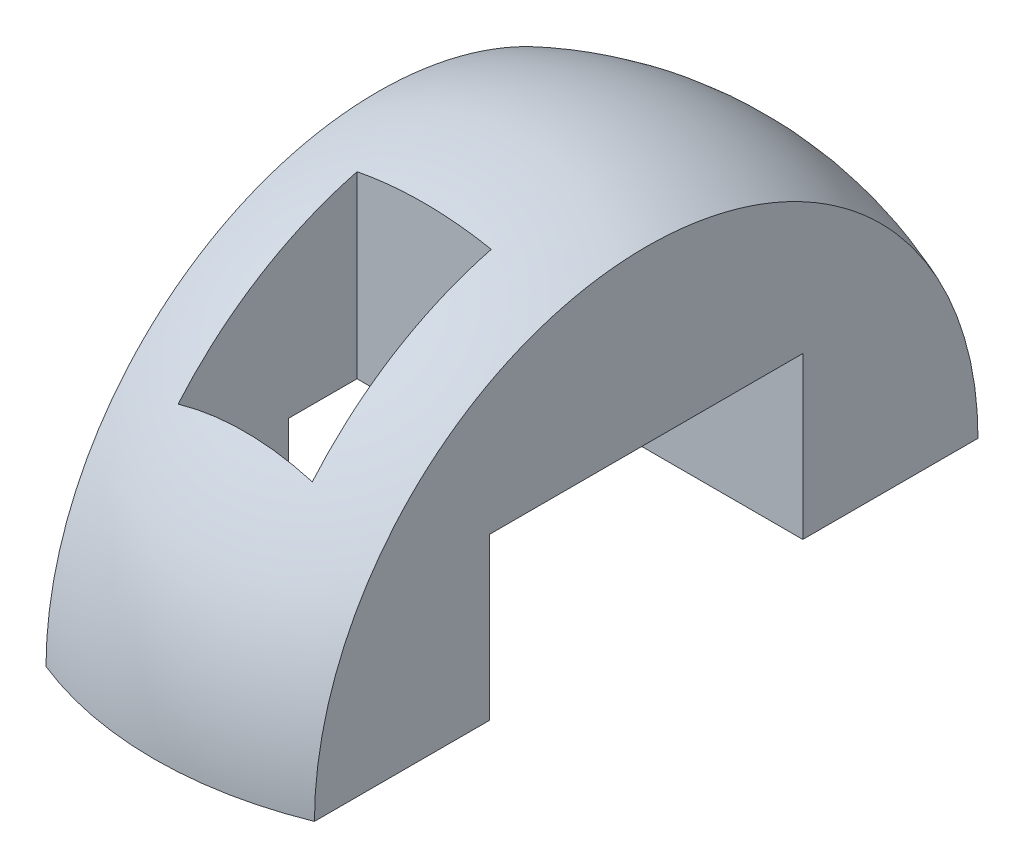
SolidWorks part; units mm, degrees
ref_plane "Front Plane" through (0, 0, 0) normal (0, 0, 1) x (1, 0, 0)
ref_plane "Top Plane" through (0, 0, 0) normal (0, 1, 0) x (1, 0, 0)
ref_plane "Right Plane" through (0, 0, 0) normal (1, 0, 0) x (0, 0, -1)
sketch "Sketch1" plane through (0, 0, 0) normal (0, 0, 1) x (1, 0, 0)
  line L0 (0, 0) -> (80, 0)
  line L1 (0, 0) -> (0, 80) construction
  line L2 (0, 0) -> (0, 80)
  line L3 (0, 80) -> (0, 0)
  arc A1 (80, 0) -> (0, 80) centre (0, 0) ccw
  dimension "D2" = 80
revolve "Revolve2" add sketch "Sketch1" angle 360 about L2
ref_plane "Plane1" through (0, 0, 80) normal (0, 0, 1) x (1, 0, 0)
sketch "Sketch2" plane through (0, 0, 80) normal (0, 0, 1) x (1, 0, 0)
  line L0 (-80, 0) -> (80, 0) construction
  line L1 (80, 0) -> (0, 0)
  line L2 (80, 0) -> (80, 80)
  line L3 (80, 80) -> (0, 80)
  line L4 (0, 0) -> (0, 80)
  line L5 (0, 80) -> (-80, 80)
  line L6 (0, 80) -> (0, 0)
  line L7 (0, 0) -> (-80, 0)
  line L8 (-80, 80) -> (-80, 0)
  line L10 (30, 0) -> (-30, 0)
  line L11 (30, 0) -> (30, 80)
  line L12 (30, 80) -> (-30, 80)
  line L13 (-30, 0) -> (-30, 80)
  arc A0 (80, 0) -> (-80, 0) centre (0, 0) ccw construction
  dimension "D1" = 60
  dimension "D2" = 50
extrude "Cut-Extrude1" cut sketch "Sketch2" against normal through all contours L11 L1 L2 L3 | L7 L13 L5 L8
sketch "Sketch3" plane through (-30, 0, 0) normal (-1, 0, 0) x (0, 0, 1)
  line L0 (-74.162, 0) -> (74.162, 0) construction
  line L1 (35, 0) -> (-35, 0)
  line L2 (35, 0) -> (35, 36)
  line L3 (35, 36) -> (-35, 36)
  line L4 (-35, 0) -> (-35, 36)
  line L5 (-80, 0) -> (80, 0)
  arc A0 (80, 0) -> (-80, 0) centre (0, 0) ccw construction
  line M4 (-74.162, 0) -> (74.162, 0)
  dimension "D1" = 36
  dimension "D2" = 70
  dimension "D3" = 45
extrude "Cut-Extrude2" cut sketch "Sketch3" against normal through all contours L4 L2 L3 M4
ref_plane "Plane2" through (0, 80, 0) normal (0, -1, 0) x (-1, 0, 0)
sketch "Sketch5" plane through (0, 80, 0) normal (0, -1, 0) x (-1, 0, 0)
  line L1 (14.9241, -59.717) -> (-15.0759, -59.717)
  line L2 (14.9241, -59.717) -> (14.9241, -19.717)
  line L3 (14.9241, -19.717) -> (-15.0759, -19.717)
  line L4 (-15.0759, -59.717) -> (-15.0759, -19.717)
  dimension "D1" = 30
  dimension "D2" = 40
extrude "Cut-Extrude3" cut sketch "Sketch5" along normal through all
